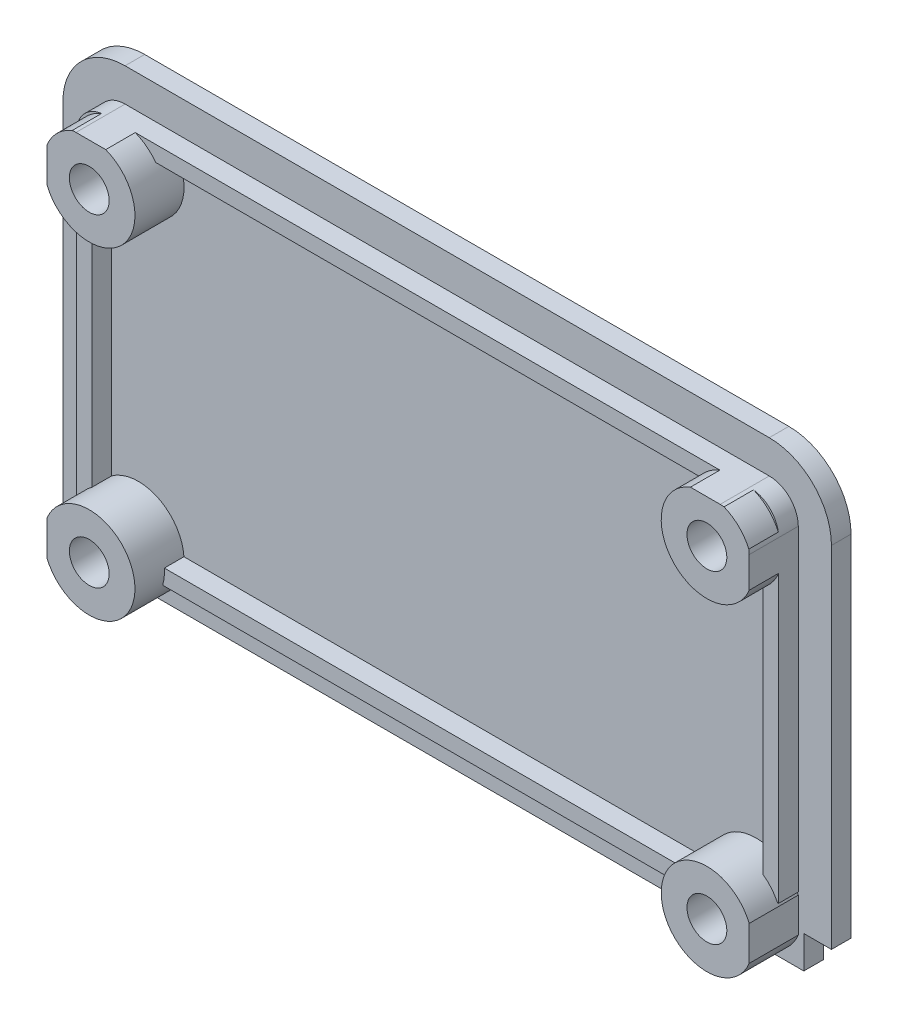
SolidWorks part; units mm, degrees
ref_plane "Front Plane" through (0, 0, 0) normal (0, 0, 1) x (1, 0, 0)
ref_plane "Top Plane" through (0, 0, 0) normal (0, 1, 0) x (1, 0, 0)
ref_plane "Right Plane" through (0, 0, 0) normal (1, 0, 0) x (0, 0, -1)
sketch "Sketch2" plane through (0, 0, 0) normal (0, 0, 1) x (1, 0, 0)
  line L0 (22.1, -10.7046) -> (21.846, -10.7046)
  line L23 (23.54, -10.7046) -> (23.54, 10.73)
  line L24 (22.1, -10.7046) -> (23.54, -10.7046)
  line L25 (22.1, 10.73) -> (22.1, -10.7046)
  line L26 (-19.73, 13.1) -> (19.73, 13.1)
  line L27 (-22.1, -10.7046) -> (-22.1, 10.73)
  line L28 (-23.54, -10.7046) -> (-22.1, -10.7046)
  line L29 (-23.54, 10.73) -> (-23.54, -10.7046)
  line L30 (19.73, 14.54) -> (-19.73, 14.54)
  line L31 (23.54, -10.7046) -> (23.54, 10.73)
  line L32 (22.1, -10.7046) -> (23.54, -10.7046)
  line L57 (-23.54, -10.7046) -> (-22.1, -10.7046)
  line L58 (-23.54, 10.73) -> (-23.54, -10.7046)
  line L59 (19.73, 14.54) -> (-19.73, 14.54)
  line L82 (21.846, -10.7046) -> (21.846, -12.6964)
  line L83 (21.846, -12.6964) -> (-21.846, -12.6964)
  line L84 (-21.846, -12.6964) -> (-21.846, -10.7046)
  line L85 (-21.846, -10.7046) -> (-22.1, -10.7046)
  arc A20 (23.54, 10.73) -> (19.73, 14.54) centre (19.73, 10.73) ccw
  arc A21 (22.1, 10.73) -> (19.73, 13.1) centre (19.73, 10.73) ccw
  arc A22 (-19.73, 13.1) -> (-22.1, 10.73) centre (-19.73, 10.73) ccw
  arc A23 (-19.73, 14.54) -> (-23.54, 10.73) centre (-19.73, 10.73) ccw
  arc A24 (23.54, 10.73) -> (19.73, 14.54) centre (19.73, 10.73) ccw
  arc A27 (-19.73, 14.54) -> (-23.54, 10.73) centre (-19.73, 10.73) ccw
  circle A38 centre (-18.9175, -9.8975) radius 2.7989 construction
  dimension "D1" = 0
  dimension "D2" = 0.254
extrude "Extrude1" add sketch "Sketch2" against normal blind 1.2
sketch "Sketch3" plane through (0, 0, 0) normal (0, 0, 1) x (1, 0, 0)
  line L5 (19.73, 12.508) -> (-19.73, 12.508)
  line L6 (19.73, 12.508) -> (-19.73, 12.508)
  line L7 (-21.508, 10.73) -> (-21.508, -8.6726)
  line L8 (-21.508, 10.73) -> (-21.508, -8.6726)
  line L9 (-21.508, -8.6726) -> (-19.814, -8.6726)
  line L10 (-21.508, -8.6726) -> (-19.814, -8.6726) construction
  line L11 (21.508, -8.6726) -> (21.508, 10.73)
  line L12 (21.508, -8.6726) -> (21.508, 10.73)
  line L16 (19.814, -10.6644) -> (19.814, -8.6726)
  line L17 (19.814, -10.6644) -> (19.814, -8.6726)
  line L18 (19.814, -8.6726) -> (21.508, -8.6726)
  line L19 (19.814, -8.6726) -> (21.508, -8.6726)
  line L20 (-19.814, -8.6726) -> (-19.814, -10.6644)
  line L21 (-19.814, -8.6726) -> (-19.814, -10.6644)
  line L22 (-19.814, -10.6644) -> (19.814, -10.6644)
  line L23 (-19.814, -10.6644) -> (19.814, -10.6644)
  arc A2 (21.508, 10.73) -> (19.73, 12.508) centre (19.73, 10.73) ccw
  arc A3 (21.508, 10.73) -> (19.73, 12.508) centre (19.73, 10.73) ccw
  arc A4 (-19.73, 12.508) -> (-21.508, 10.73) centre (-19.73, 10.73) ccw
  arc A5 (-19.73, 12.508) -> (-21.508, 10.73) centre (-19.73, 10.73) ccw
  dimension "D1" = 2.032
extrude "Extrude-Thin1" add sketch "Sketch3" along normal blind 1.2 thin thin type one direction reverse wall 0.96
sketch "Sketch9" plane through (0, 0, 0) normal (0, 0, 1) x (1, 0, 0)
  line L0 (0, 0) -> (-53.325, 0) construction
  circle A0 centre (18.9175, -9.8975) radius 2.7989
  circle A1 centre (-18.9175, -9.8975) radius 2.7989
  circle A3 centre (-18.9175, 9.8975) radius 2.7989
  circle A4 centre (-18.9175, 9.8975) radius 2.7989
  circle A7 centre (18.9175, 9.8975) radius 2.7989
  circle A8 centre (18.9175, 9.8975) radius 2.7989
  dimension "D2" = 0
  dimension "D4" = 0
extrude "Extrude3" add sketch "Sketch9" along normal up to surface (3.008 mm away)
sketch "Sketch11" plane through (0, 0, 0) normal (0, 0, 1) x (1, 0, 0)
  line L0 (-21.508, 10.73) -> (-21.508, -8.6726) construction
  line L1 (19.73, 12.508) -> (-19.73, 12.508) construction
  line L2 (21.508, -8.6726) -> (21.508, 10.73) construction
  line L3 (-21.508, 10.73) -> (-21.508, -12.6964)
  line L4 (19.73, 12.508) -> (-19.73, 12.508)
  line L5 (21.508, -12.6964) -> (21.508, 10.73)
  line L8 (-21.508, -12.6964) -> (21.508, -12.6964)
  line L9 (18.9175, -12.6964) -> (21.846, -12.6964) construction
  arc A0 (-19.73, 12.508) -> (-21.508, 10.73) centre (-19.73, 10.73) ccw construction
  arc A1 (21.508, 10.73) -> (19.73, 12.508) centre (19.73, 10.73) ccw construction
  arc A2 (-19.73, 12.508) -> (-21.508, 10.73) centre (-19.73, 10.73) ccw
  arc A3 (21.508, 10.73) -> (19.73, 12.508) centre (19.73, 10.73) ccw
extrude "Cut-Extrude2" cut sketch "Sketch11" along normal through all flip side to cut
hole_wizard "CSK for #2 Flat Head Machine Screw1" positions "Sketch6" profile "Sketch7" countersink size "#2" standard "ANSI Inch" end condition through all
sketch "Sketch6" plane through (0, 0, -1.2) normal (0, 0, -1) x (-1, 0, 0)
  point P0 (-18.9175, 9.8975)
  point P2 (-18.9175, -9.8975)
  point P4 (18.9175, -9.8975)
  point P6 (18.9175, 9.8975)
sketch "Sketch7" plane through (18.9175, 9.8975, -1.2) normal (1, 0, 0) x (0, 1, 0)
  line L0 (0, 0) -> (0, 4.208)
  line L1 (0, 4.208) -> (1.2192, 4.208)
  line L2 (1.2192, 4.208) -> (1.2192, 1.3643)
  line L3 (1.2192, 1.3643) -> (2.1844, 0.254)
  line L4 (2.1844, 0.254) -> (2.1844, 0)
  line L6 (2.1844, 0) -> (0, 0)
  line L7 (-1.2192, 1.3643) -> (-2.1844, 0.254) construction
  line L11 (0, -6.35) -> (0, 107.95) construction
  dimension "Thru Hole Dia." = 2.4384
  dimension "Thru Hole Depth" = 4.208
  dimension "C'Sink Dia." = 4.3688
  dimension "C'Sink Angle" = 82
  dimension "Head Clearance" = 0.254
